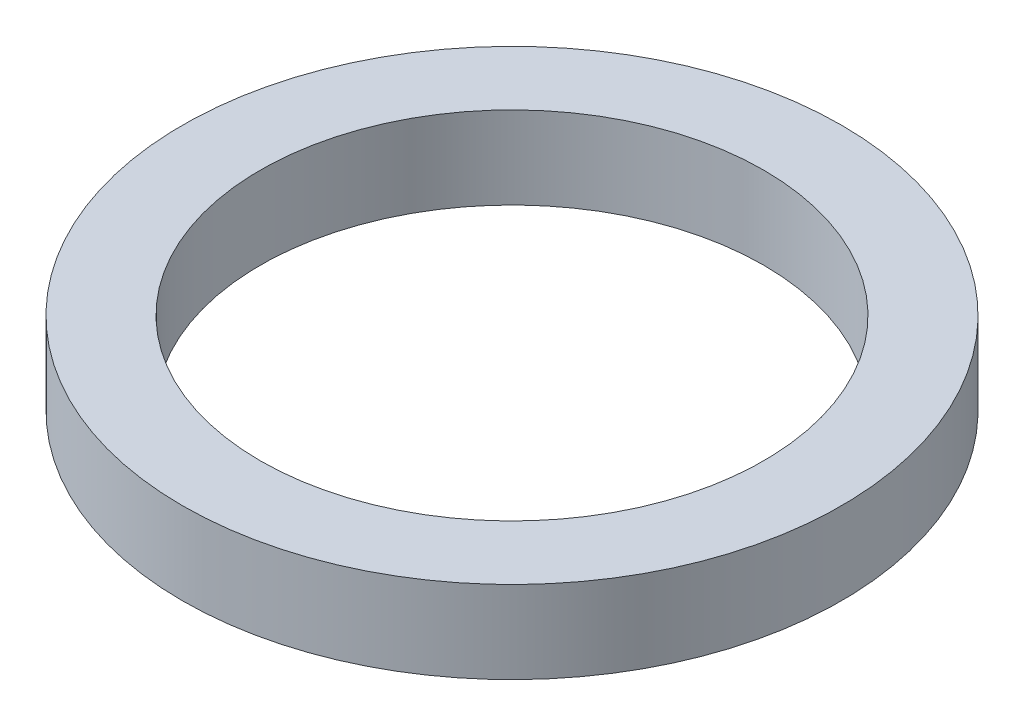
SolidWorks part; units mm, degrees
ref_plane "Front Plane" through (0, 0, 0) normal (0, 0, 1) x (1, 0, 0)
ref_plane "Top Plane" through (0, 0, 0) normal (0, 1, 0) x (1, 0, 0)
ref_plane "Right Plane" through (0, 0, 0) normal (1, 0, 0) x (0, 0, -1)
sketch "Sketch1" plane through (0, 0, 0) normal (0, 1, 0) x (1, 0, 0)
  circle A0 centre (0, 0) radius 27.5
  circle A1 centre (0, 0) radius 36
  dimension "D1" = 55
  dimension "D2" = 72
extrude "Boss-Extrude1" add sketch "Sketch1" along normal blind 9
